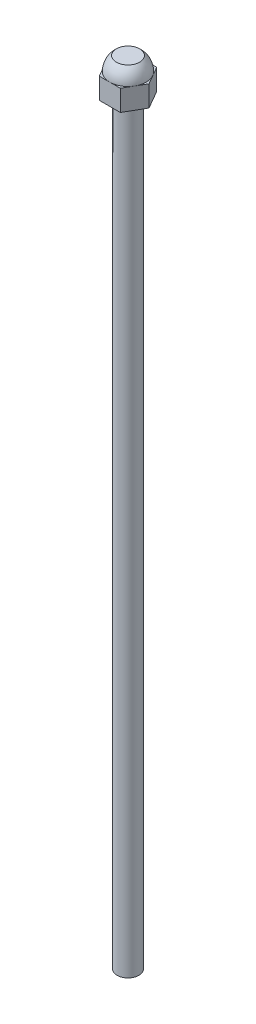
SolidWorks part; units mm, degrees
ref_plane "Front Plane" through (0, 0, 0) normal (0, 0, 1) x (1, 0, 0)
ref_plane "Top Plane" through (0, 0, 0) normal (0, 1, 0) x (1, 0, 0)
ref_plane "Right Plane" through (0, 0, 0) normal (1, 0, 0) x (0, 0, -1)
sketch "Sketch1" plane through (0, 0, 0) normal (0, 1, 0) x (1, 0, 0)
  circle A0 centre (0, 0) radius 3.9
  dimension "D1" = 7.8
extrude "Boss-Extrude1" add sketch "Sketch1" along normal blind 270
sketch "Sketch2" plane through (0, 270, 0) normal (0, 1, 0) x (1, 0, 0)
  line L0 (0, 0) -> (7.5056, 0) construction
  line L1 (7.5056, 0) -> (3.7528, 6.5)
  line L2 (3.7528, 6.5) -> (-3.7528, 6.5)
  line L3 (-3.7528, 6.5) -> (-7.5056, 0)
  line L4 (-7.5056, 0) -> (-3.7528, -6.5)
  line L5 (-3.7528, -6.5) -> (3.7528, -6.5)
  line L6 (3.7528, -6.5) -> (7.5056, 0)
  circle A0 centre (0, 0) radius 6.5 construction
  dimension "D1" = 13
extrude "Boss-Extrude2" add sketch "Sketch2" along normal blind 7.5
ref_plane "Plane2" through (0, 0, 0) normal (0.5, 0, 0.866) x (0.866, 0, -0.5)
sketch "Sketch5" plane through (0, 0, 0) normal (0.5, 0, 0.866) x (0.866, 0, -0.5)
  line L1 (0, 277.5) -> (6.5, 277.5)
  line L3 (0, 282.5) -> (4.1533, 282.5)
  line L4 (0, 282.5) -> (0, 277.5)
  arc A1 (6.5, 277.5) -> (4.1533, 282.5) centre (0, 277.5) ccw
  point P12 (2.0767, 282.5)
  dimension "D1" = 5
revolve "Revolve2" add sketch "Sketch5" angle 360 about L4
